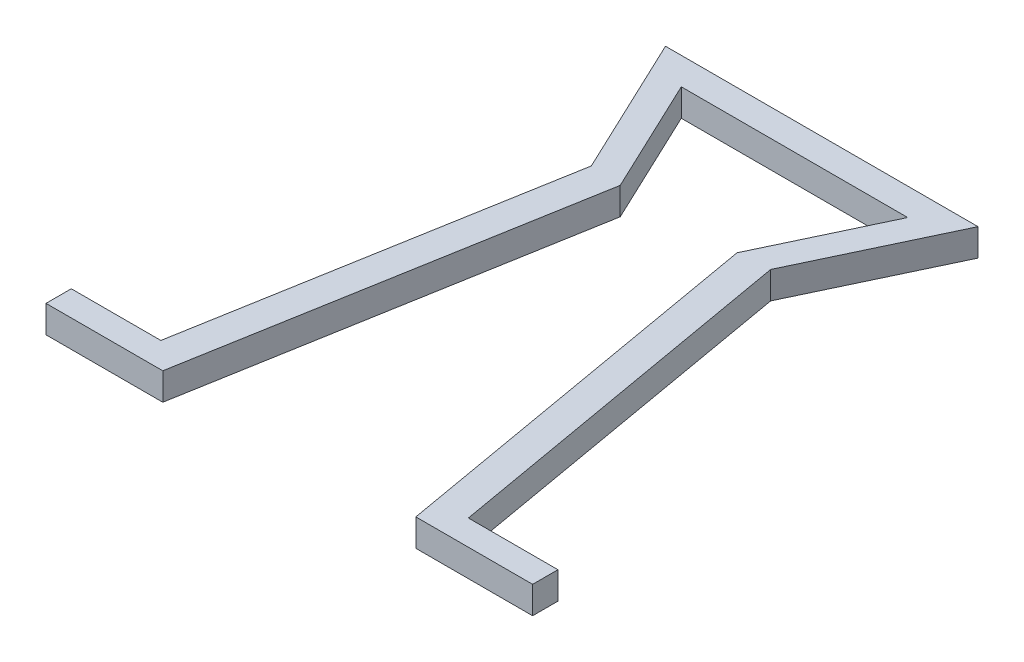
SolidWorks part; units mm, degrees
ref_plane "Front Plane" through (0, 0, 0) normal (0, 0, 1) x (1, 0, 0)
ref_plane "Top Plane" through (0, 0, 0) normal (0, 1, 0) x (1, 0, 0)
ref_plane "Right Plane" through (0, 0, 0) normal (1, 0, 0) x (0, 0, -1)
sketch "Sketch1" plane through (0, 0, 0) normal (0, 1, 0) x (1, 0, 0)
  line L0 (-15.24, 0) -> (-7.62, 0)
  line L1 (-55, 0) -> (55, 0) construction
  line L2 (-7.62, 0) -> (-3.175, 25.4)
  line L6 (4.445, 25.4) -> (8.89, 0)
  line L7 (8.89, 0) -> (16.51, 0)
  line L8 (16.51, 0) -> (16.51, 1.651)
  line L9 (16.51, 1.651) -> (10.668, 1.651)
  line L15 (-9.398, 1.651) -> (-15.24, 1.651)
  line L16 (-15.24, 1.651) -> (-15.24, 0)
  line L17 (0, -55) -> (0, 55) construction
  line L18 (-9.398, 1.651) -> (-5.2149, 25.5543)
  line L19 (10.668, 1.651) -> (6.4849, 25.5543)
  line L20 (6.4849, 25.5543) -> (10.8295, 34.7386)
  line L21 (4.445, 25.4) -> (8.0215, 32.9606)
  line L22 (-5.2149, 25.5543) -> (-9.5595, 34.7386)
  line L23 (-3.175, 25.4) -> (-6.7515, 32.9606)
  line L24 (-9.5595, 34.7386) -> (10.8295, 34.7386)
  line L25 (8.0215, 32.9606) -> (-6.7515, 32.9606)
  dimension "D1" = 31.75
  dimension "D2" = 15.24
  dimension "D3" = 16.51
  dimension "D4" = 7.62
  dimension "D5" = 25.4
  dimension "D6" = 1.651
  dimension "D7" = 1.778
  dimension "D8" = 1.778
  dimension "D9" = 10.16
  dimension "D10" = 1.778
extrude "Boss-Extrude1" add sketch "Sketch1" along normal blind 1.778
